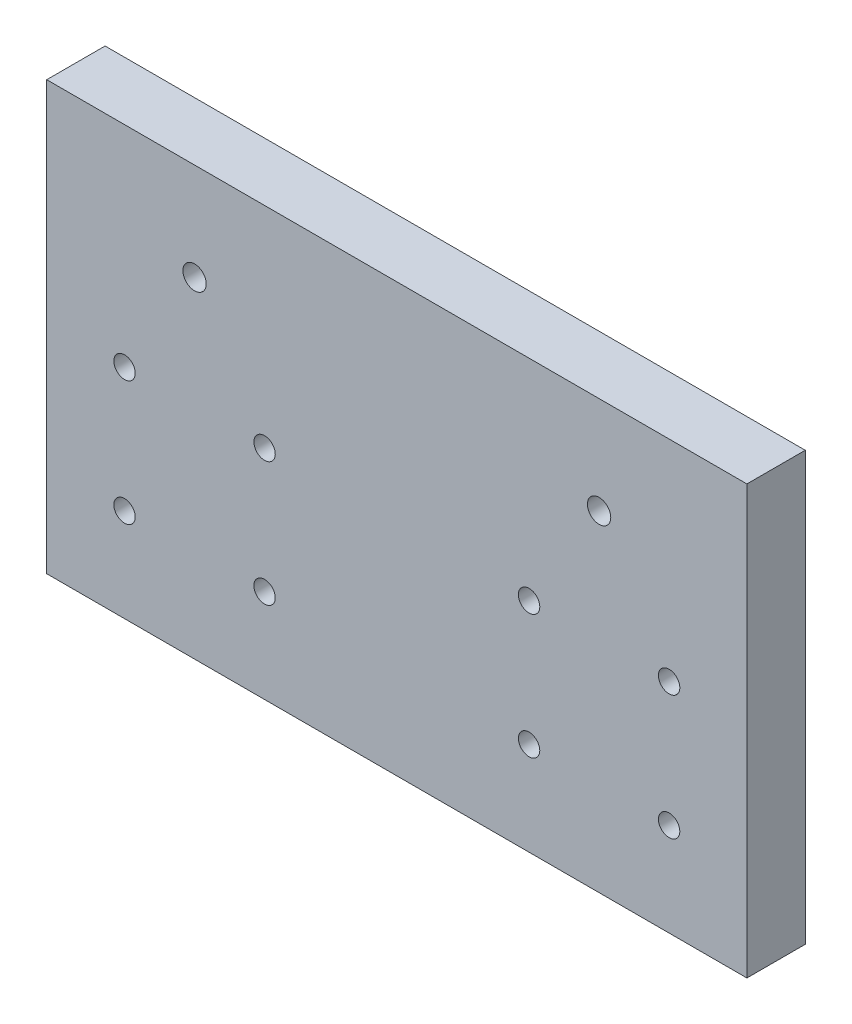
SolidWorks part; units mm, degrees
material "3.3545 (EN-AW 5086)"
ref_plane "Ebene vorne" through (0, 0, 0) normal (0, 0, 1) x (1, 0, 0)
ref_plane "Ebene oben" through (0, 0, 0) normal (0, 1, 0) x (1, 0, 0)
ref_plane "Ebene rechts" through (0, 0, 0) normal (1, 0, 0) x (0, 0, -1)
sketch "Skizze1" plane through (0, 0, 0) normal (0, 0, 1) x (1, 0, 0)
  line L0 (0, 0) -> (0, 306.9421) construction
  line L1 (-90, 0) -> (90, 0)
  line L2 (-90, 0) -> (-90, 110)
  line L3 (-90, 110) -> (90, 110)
  line L4 (90, 0) -> (90, 110)
  dimension "D1" = 110
  dimension "D2" = 180
extrude "Aufsatz-Linear austragen1" add sketch "Skizze1" along normal blind 15
sketch "Skizze2" plane through (0, 0, 15) normal (0, 0, 1) x (1, 0, 0)
  line L0 (0, 0) -> (0, 132.3712) construction
  line L1 (0, 40) -> (108.2524, 40) construction
  line L2 (34, 24) -> (70, 24) construction
  line L3 (-90, 0) -> (90, 0) construction
  circle A0 centre (34, 24) radius 2.75
  circle A1 centre (70, 24) radius 2.75
  circle A2 centre (70, 56) radius 2.75
  circle A3 centre (34, 56) radius 2.75
  circle A4 centre (-34, 24) radius 2.75
  circle A5 centre (-70, 24) radius 2.75
  circle A6 centre (-70, 56) radius 2.75
  circle A7 centre (-34, 56) radius 2.75
  dimension "D1" = 68
  dimension "D2" = 36
  dimension "D3" = 32
  dimension "D5" = 5.5
  dimension "D4" = 24
extrude "Schnitt-Linear austragen1" cut sketch "Skizze2" against normal blind 40
sketch "Skizze3" plane through (0, 0, 15) normal (0, 0, 1) x (1, 0, 0)
  line L0 (0, 0) -> (0, 120.9044) construction
  line L1 (90, 0) -> (90, 110) construction
  line L2 (90, 110) -> (-90, 110) construction
  circle A0 centre (52, 85) radius 3
  circle A1 centre (-52, 85) radius 3
  dimension "D3" = 6
  dimension "D1" = 38
  dimension "D2" = 25
extrude "Schnitt-Linear austragen2" cut sketch "Skizze3" against normal blind 40
